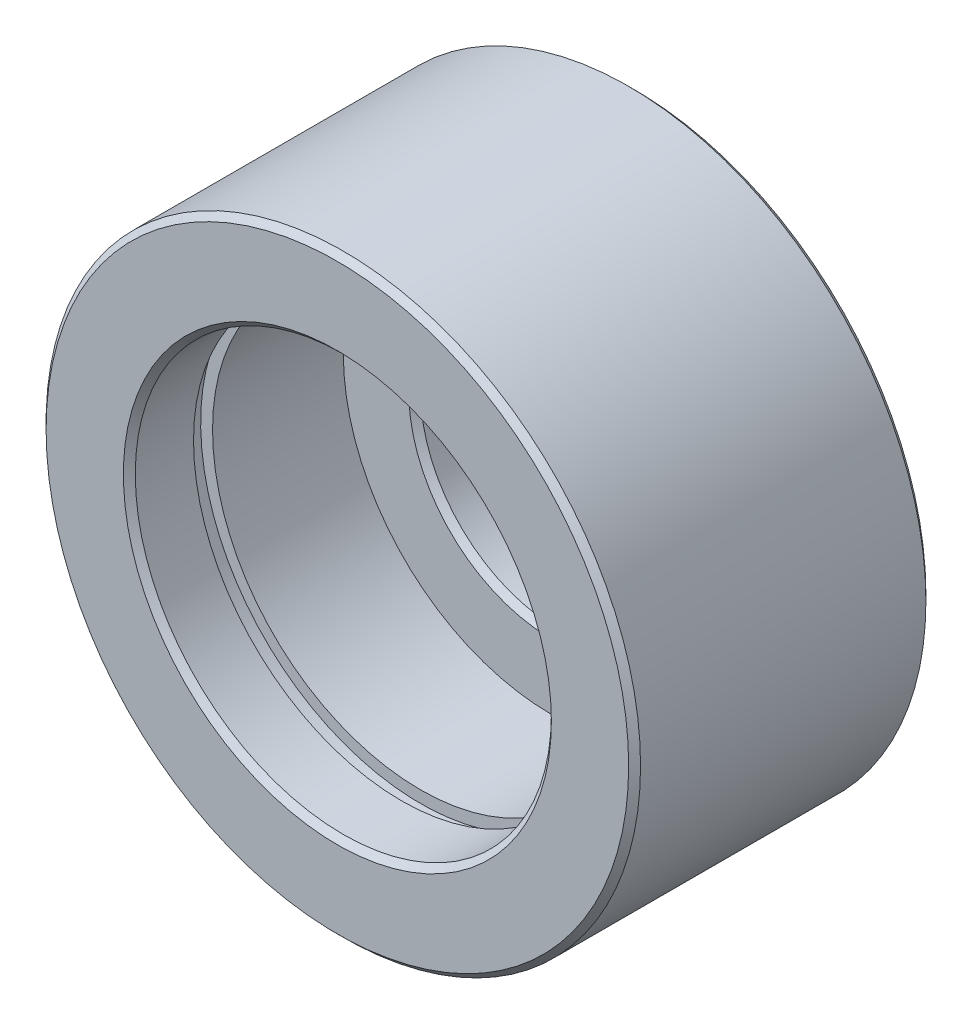
SolidWorks part; units mm, degrees
material "ASTM A36 Aço"
ref_plane "Plano frontal" through (0, 0, 0) normal (0, 0, 1) x (1, 0, 0)
ref_plane "Plano superior" through (0, 0, 0) normal (0, 1, 0) x (1, 0, 0)
ref_plane "Plano direito" through (0, 0, 0) normal (1, 0, 0) x (0, 0, -1)
sketch "Esboço1" plane through (0, 0, 0) normal (0, 0, 1) x (1, 0, 0)
  circle A0 centre (0, 0) radius 25
  dimension "D1" = 50
extrude "Ressalto-extrusão1" add sketch "Esboço1" along normal mid plane 25
sketch "Esboço2" plane through (0, 0, 0) normal (1, 0, 0) x (0, 0, -1)
  line L0 (-12.5, 25) -> (-9.5, 25) construction
  line L1 (12.5, 25) -> (-12.5, 25) construction
  line L2 (-9.5, 25) -> (0, 24.5)
  line L3 (0, 24.5) -> (9.5, 25)
  line L4 (9.5, 25) -> (12.5, 25) construction
  line L5 (-12.5, 25) -> (-12.5, -25) construction
  line L6 (-9.5, 25) -> (9.5, 25)
  dimension "D1" = 3
  dimension "D2" = 24.5
revolve "Corte-Revolução1" [suppressed] cut sketch "Esboço2" angle 360
sketch "Esboço3" plane through (0, 0, 12.5) normal (0, 0, 1) x (1, 0, 0)
  circle A0 centre (0, 0) radius 11.5
  dimension "D1" = 23
extrude "Corte-extrusão1" cut sketch "Esboço3" against normal blind 25
sketch "Esboço4" plane through (0, 0, 12.5) normal (0, 0, 1) x (1, 0, 0)
  circle A0 centre (0, 0) radius 17.5
  dimension "D1" = 35
extrude "Corte-extrusão2" cut sketch "Esboço4" against normal blind 18
chamfer "Chanfro1" distance 0.5 angle 45 5 edges at (25, 0, -12.5) (11.5, 0, -12.5) (25, 0, 12.5) (17.5, 0, 12.5) (11.5, 0, -5.5)
sketch "Esboço5" plane through (0, 0, 0) normal (1, 0, 0) x (0, 0, -1)
  line L0 (-7.1, 0) -> (-7.1, 18.5)
  line L1 (-7.1, 18.5) -> (-5.5, 18.5)
  line L2 (-5.5, 18.5) -> (-5.5, 0)
  line L3 (-5.5, 0) -> (-7.1, 0) construction
  line L4 (5.5, 17.5) -> (5.5, -17.5) construction
  line L5 (5.5, 17.5) -> (5.5, -17.5) construction
  line L6 (-5.5, 0) -> (-7.1, 0)
  dimension "D1" = 37
  dimension "D2" = 11
  dimension "D3" = 1.6
revolve "Corte-Revolução2" cut sketch "Esboço5" angle 360 about L6
